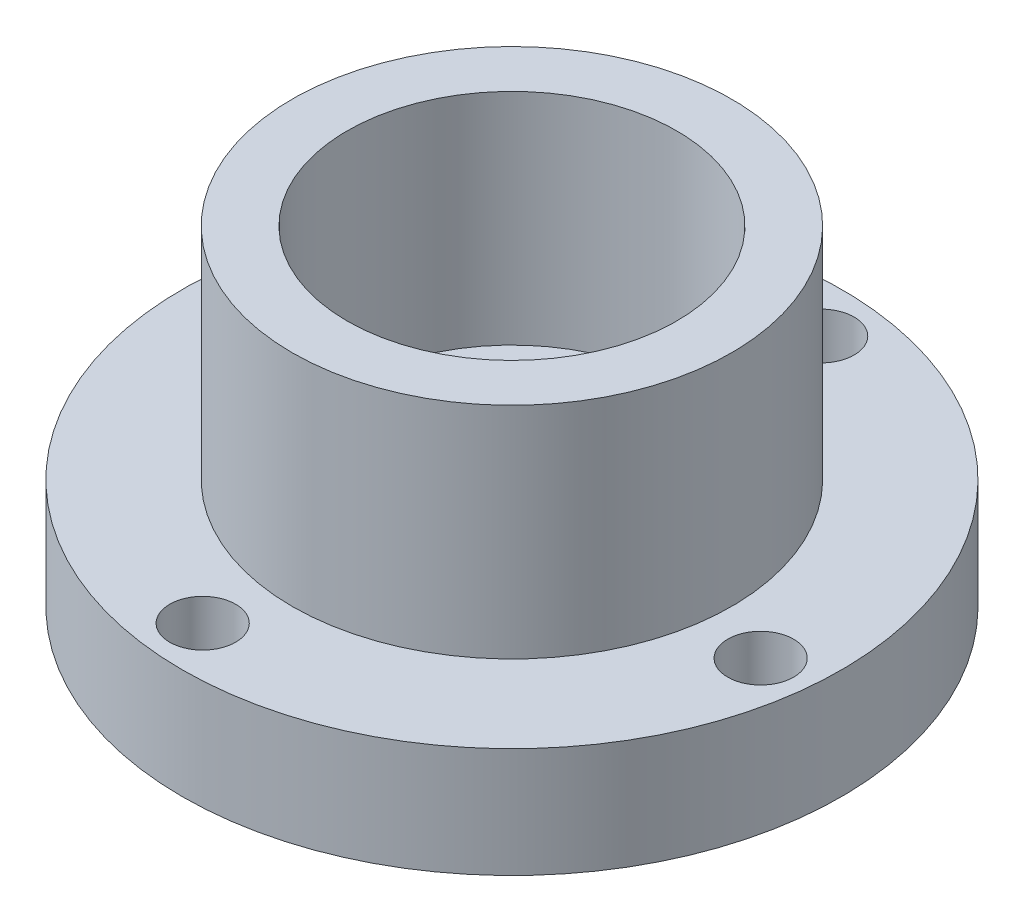
SolidWorks part; units mm, degrees
ref_plane "Front Plane" through (0, 0, 0) normal (0, 0, 1) x (1, 0, 0)
ref_plane "Top Plane" through (0, 0, 0) normal (0, 1, 0) x (1, 0, 0)
ref_plane "Right Plane" through (0, 0, 0) normal (1, 0, 0) x (0, 0, -1)
sketch "Sketch1" plane through (0, 0, 0) normal (0, 1, 0) x (1, 0, 0)
  circle A0 centre (0, 0) radius 15
  circle A1 centre (-12.6977, 1.3772) radius 1.5
  circle A2 centre (1.3772, 12.6977) radius 1.5
  circle A3 centre (12.6977, -1.3772) radius 1.5
  circle A4 centre (-1.3772, -12.6977) radius 1.5
  point P14 (0, 0)
  dimension "D1" = 4
  dimension "D2" = 30
extrude "Boss-Extrude1" add sketch "Sketch1" along normal blind 5
sketch "Sketch2" plane through (0, 5, 0) normal (0, 1, 0) x (1, 0, 0)
  circle A0 centre (0, 0) radius 10
  circle A1 centre (0, 0) radius 7.5
  dimension "D1" = 15
  dimension "D2" = 20
extrude "Boss-Extrude2" add sketch "Sketch2" along normal blind 10
